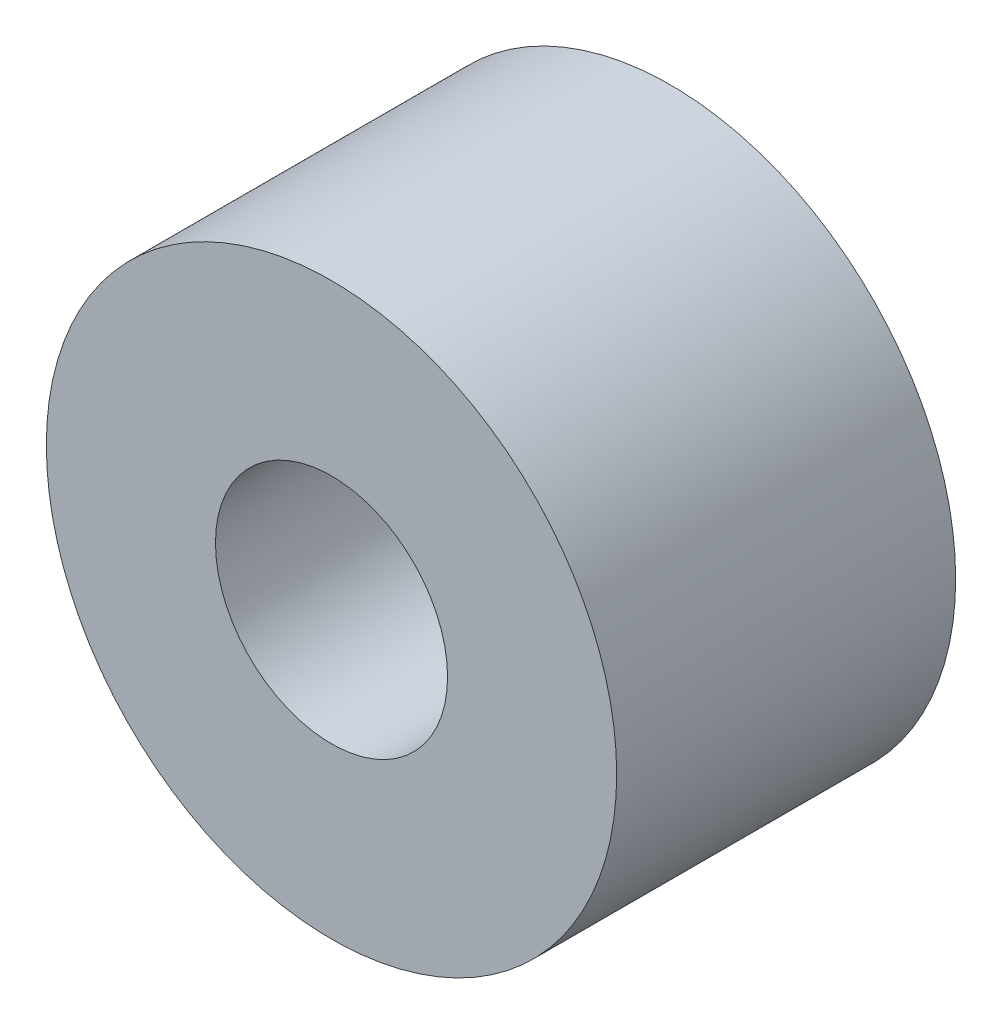
SolidWorks part; units mm, degrees
ref_plane "Front Plane" through (0, 0, 0) normal (0, 0, 1) x (1, 0, 0)
ref_plane "Top Plane" through (0, 0, 0) normal (0, 1, 0) x (1, 0, 0)
ref_plane "Right Plane" through (0, 0, 0) normal (1, 0, 0) x (0, 0, -1)
sketch "Sketch1" plane through (0, 0, 3.175) normal (0, 0, 1) x (1, 0, 0)
  circle A1 centre (0, 0) radius 4.915
  circle A2 centre (0, 0) radius 2
  circle A3 centre (0, 0) radius 4.915 construction
  dimension "D1" = 4
extrude "Boss-Extrude1" add sketch "Sketch1" along normal blind 5.842 contours A1 A2
